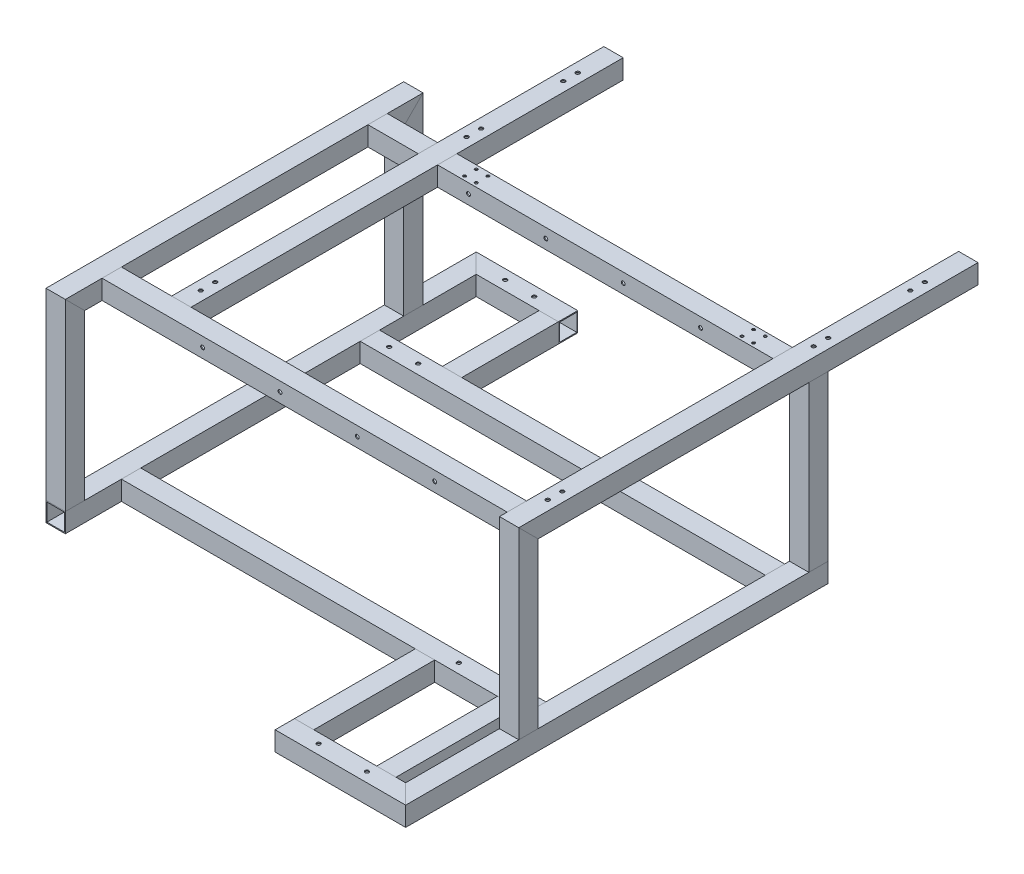
SolidWorks part; units mm, degrees
ref_plane "Front" through (0, 0, 0) normal (0, 0, 1) x (1, 0, 0)
ref_plane "Top" through (0, 0, 0) normal (0, 1, 0) x (1, 0, 0)
ref_plane "Right" through (0, 0, 0) normal (1, 0, 0) x (0, 0, -1)
sketch3d "3D草图2"
  line L0 (0, 0, 0) -> (0, 0, -430) construction
  line L1 (0, 0, 0) -> (0, 190, 0)
  line L2 (0, 190, 0) -> (0, 190, -465)
  line L3 (0, 190, -300) -> (0, 0, -300)
  line L4 (-115, 0, 117) -> (-115, 0, -28)
  line L5 (-30, 0, -28) -> (-30, 0, 117)
  line L7 (-439, 190, 30) -> (-439, 0, 30)
  line L8 (-439, 190, 30) -> (-439, 190, -320)
  line L9 (-439, 190, -320) -> (-439, 0, -320)
  line L10 (-439, 190, -283) -> (0, 190, -283) construction
  line L11 (-367, 190, 30) -> (-367, 190, -465) construction
  line L13 (-439, 190, -283) -> (-367, 190, -283)
  line L14 (-367, 190, -283) -> (0, 190, -283)
  line L16 (0, 0, 0) -> (0, 0, 117) construction
  line L17 (0, 0, 117) -> (-115, 0, 117) construction
  line L20 (-439, 0, -395) -> (-347, 0, -395) construction
  line L22 (0, 0, 117) -> (-439, 0, 117)
  line L23 (-439, 0, 117) -> (-439, 0, -395)
  line L24 (-439, 0, -395) -> (0, 0, -395)
  line L25 (0, 0, -395) -> (0, 0, 117)
  line L26 (-439, 0, -28) -> (0, 0, -28)
  line L27 (-439, 190, -8) -> (0, 190, -8)
  line L28 (-439, 0, -275) -> (0, 0, -275)
  line L29 (-367, 190, -8) -> (-367, 190, -465)
  dimension "D1" = 430
  dimension "D2" = 190
  dimension "D3" = 465
  dimension "D4" = 300
  dimension "D5" = 90
  dimension "D6" = 439
  dimension "D7" = 439
  dimension "D8" = 350
  dimension "D9" = 37
  dimension "D10" = 495
  dimension "D11" = 72
  dimension "D12" = 350
  dimension "D21" = 145
  dimension "D13" = 117
  dimension "D14" = 115
  dimension "D15" = 120
  dimension "D16" = 0
  dimension "D17" = 90
  dimension "D18" = 38
  dimension "D19" = 8
  dimension "D20" = 25
  dimension "D24" = 115
  dimension "D22" = 0
  dimension "D25" = 72
  dimension "D26" = 30
other " F:\\SOLIDWORKS2016\\SOLIDWORKS\\LANG\\CHINESE-SIMPLIFIED\\WELDMENT PROFILES\\GB\\铝管\\20X20X1 - 丢失(1)"
ref_plane "基准面3" through (0, 0, 117) normal (-1, 0, 0) x (0, 0, 1)
sketch "草图12" plane through (0, 0, 117) normal (-1, 0, 0) x (0, 0, 1)
  line L1 (-10, -10) -> (10, -10)
  line L2 (-10, -10) -> (-10, 10)
  line L3 (-10, 10) -> (10, 10)
  line L4 (10, -10) -> (10, 10)
  line L5 (-10, -10) -> (10, 10) construction
  line L6 (-10, 10) -> (10, -10) construction
  line L7 (-9, -9) -> (9, -9)
  line L8 (-9, -9) -> (-9, 9)
  line L9 (-9, 9) -> (9, 9)
  line L10 (9, -9) -> (9, 9)
  line L11 (-9, -9) -> (9, 9) construction
  line L12 (-9, 9) -> (9, -9) construction
  point P0 (0, 0)
  point P6 (0, 0)
  point P11 (0, 0)
  dimension "D1" = 20
  dimension "D2" = 20
  dimension "D3" = 18
  dimension "D4" = 18
sketch "草图13" plane through (0, 10, 0) normal (0, 1, 0) x (1, 0, 0)
  line L0 (0, -117) -> (-176.0198, -117) construction
  line L1 (-10, -107) -> (10, -127) construction
  line L2 (-10, 28) -> (-176.0198, 28) construction
  line L3 (-10, 18) -> (-10, 38) construction
  circle A0 centre (-90, 28) radius 2
  circle A1 centre (-40, 28) radius 2
  circle A2 centre (-90, -117) radius 2
  circle A3 centre (-40, -117) radius 2
  dimension "D1" = 4
  dimension "D2" = 4
  dimension "D3" = 4
  dimension "D4" = 4
  dimension "D5" = 30
  dimension "D6" = 50
extrude "切除-拉伸1" cut sketch "草图13" against normal through all
sketch "草图14" plane through (0, 10, 0) normal (0, 1, 0) x (1, 0, 0)
  line L0 (-439, 395) -> (-377.9377, 395) construction
  line L1 (-449, 405) -> (-429, 385) construction
  line L2 (-429, 275) -> (-377, 275) construction
  line L3 (-429, 273) -> (-429, 293) construction
  line L5 (-429, 285) -> (-429, 265) construction
  circle A0 centre (-379, 275) radius 2
  circle A1 centre (-409, 275) radius 2
  circle A2 centre (-409, 395) radius 2
  circle A3 centre (-379, 395) radius 2
  dimension "D1" = 4
  dimension "D2" = 4
  dimension "D4" = 4
  dimension "D5" = 4
  dimension "D3" = 30
  dimension "D6" = 20
extrude "切除-拉伸2" cut sketch "草图14" against normal through all
sketch "草图16" plane through (0, 200, 0) normal (0, 1, 0) x (1, 0, 0)
  circle A0 centre (0, 420) radius 2
  circle A1 centre (0, 405) radius 2
  circle A2 centre (0, 320) radius 2
  circle A3 centre (0, 305) radius 2
  circle A4 centre (0, 45) radius 2
  circle A5 centre (0, 30) radius 2
  dimension "D1" = 4
  dimension "D2" = 4
  dimension "D3" = 4
  dimension "D4" = 4
  dimension "D5" = 4
  dimension "D6" = 4
extrude "切除-拉伸4" cut sketch "草图16" against normal up to surface (20 mm away) up to face at (0, 180, -237.5)
sketch "草图23" plane through (0, 10, 0) normal (0, 1, 0) x (1, 0, 0)
  line L0 (10, 405) -> (-449, 405) construction
  line L1 (10, 310) -> (-344, 310)
  line L2 (10, 310) -> (10, 405)
  line L3 (10, 405) -> (-344, 405)
  line L4 (-344, 310) -> (-344, 405)
  line L6 (-449, 405) -> (-449, -127) construction
  dimension "D1" = 105
extrude "切除-拉伸10" cut sketch "草图23" against normal through all
sketch "草图24" plane through (0, 10, 0) normal (0, 1, 0) x (1, 0, 0)
  line L0 (-344, 285) -> (-344, 385)
  line L1 (-344, 385) -> (-364, 385)
  line L2 (-344, 385) -> (-429, 385) construction
  line L3 (-344, 285) -> (-364, 285)
  line L4 (-364, 385) -> (-364, 285)
  line L5 (-10, 285) -> (-429, 285) construction
  dimension "D1" = 20
extrude "凸台-拉伸2" add sketch "草图24" against normal blind 20 separate body
sketch "草图25" plane through (0, 200, 0) normal (0, 1, 0) x (1, 0, 0)
  line L0 (-357, 465) -> (-357, 18) construction
  line L2 (-10, 18) -> (-429, 18) construction
  circle A0 centre (-367, 38) radius 2
  circle A1 centre (-367, 53) radius 2
  circle A2 centre (-367, 328) radius 2
  circle A3 centre (-367, 313) radius 2
  circle A4 centre (-367, 428) radius 2
  circle A5 centre (-367, 413) radius 2
  dimension "D1" = 15
  dimension "D2" = 15
  dimension "D3" = 15
  dimension "D4" = 10
  dimension "D5" = 10
  dimension "D6" = 10
  dimension "D7" = 10
  dimension "D8" = 10
  dimension "D9" = 10
  dimension "D10" = 100
  dimension "D11" = 275
  dimension "D12" = 20
  dimension "D13" = 4
  dimension "D14" = 4
  dimension "D15" = 4
  dimension "D16" = 4
  dimension "D17" = 4
  dimension "D18" = 4
extrude "切除-拉伸11" cut sketch "草图25" against normal blind 20
sketch "草图27" plane through (0, 0, 2) normal (0, 0, 1) x (1, 0, 0)
  line L0 (-357, 180) -> (-357, 200) construction
  line L1 (-10, 200) -> (-429, 200) construction
  circle A0 centre (-325, 190) radius 2
  circle A1 centre (-245, 190) radius 2
  circle A2 centre (-165, 190) radius 2
  circle A3 centre (-85, 190) radius 2
  dimension "D1" = 32
  dimension "D2" = 80
  dimension "D3" = 80
  dimension "D4" = 80
  dimension "D5" = 10
  dimension "D6" = 10
  dimension "D7" = 10
  dimension "D8" = 10
  dimension "D9" = 4
  dimension "D10" = 4
  dimension "D11" = 4
  dimension "D12" = 4
extrude "切除-拉伸12" cut sketch "草图27" against normal through all
sketch "草图28" plane through (0, 10, 0) normal (0, 1, 0) x (1, 0, 0)
  line L0 (-125, -107) -> (-125, -127)
  line L1 (-449, -127) -> (10, -127) construction
  line L2 (-125, -127) -> (-449, -127)
  line L3 (-449, -127) -> (-449, -40)
  line L4 (-449, -40) -> (-429, -40)
  line L5 (-429, -40) -> (-125, -107)
extrude "切除-拉伸13" cut sketch "草图28" against normal blind 20
sketch "草图29" plane through (0, 200, 0) normal (0, 1, 0) x (1, 0, 0)
  line L0 (-10, 465) -> (-10, -10) construction
  line L1 (-10, 293) -> (-357, 293) construction
  line L2 (-183.5, 319.819) -> (-183.5, 236.4886) construction
  circle A0 centre (-46, 289) radius 1.5
  circle A1 centre (-34, 289) radius 1.5
  circle A2 centre (-34, 277) radius 1.5
  circle A3 centre (-46, 277) radius 1.5
  circle A4 centre (-321, 277) radius 1.5
  circle A5 centre (-333, 277) radius 1.5
  circle A6 centre (-333, 289) radius 1.5
  circle A7 centre (-321, 289) radius 1.5
  dimension "D1" = 12
  dimension "D2" = 12
  dimension "D3" = 24
  dimension "D4" = 24
  dimension "D5" = 12
  dimension "D6" = 12
  dimension "D7" = 4
  dimension "D8" = 4
  dimension "D9" = 3
  dimension "D10" = 3
  dimension "D11" = 3
  dimension "D12" = 3
extrude "切除-拉伸14" cut sketch "草图29" against normal blind 20
